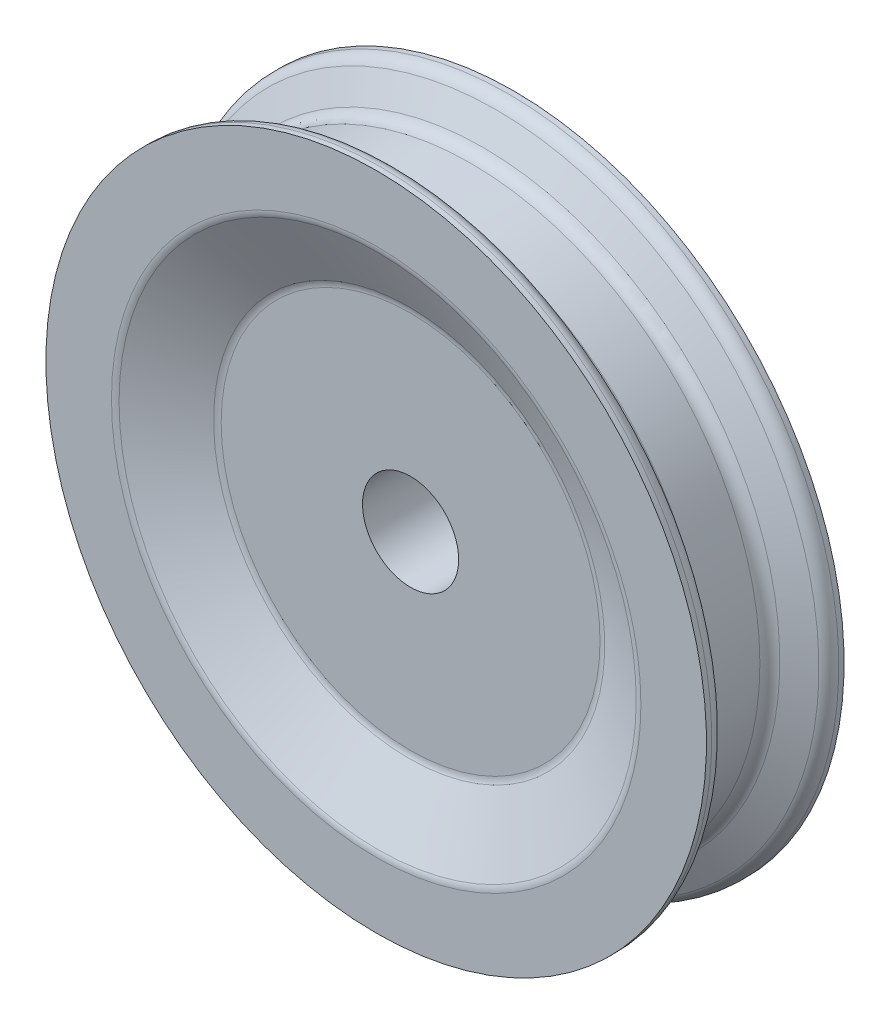
SolidWorks part; units mm, degrees
ref_plane "Front Plane" through (0, 0, 0) normal (0, 0, 1) x (1, 0, 0)
ref_plane "Top Plane" through (0, 0, 0) normal (0, 1, 0) x (1, 0, 0)
ref_plane "Right Plane" through (0, 0, 0) normal (1, 0, 0) x (0, 0, -1)
sketch "Sketch1" plane through (0, 0, 0) normal (1, 0, 0) x (0, 0, -1)
  line L0 (-25, 120) -> (-25, 95)
  line L1 (-12.5, 0) -> (12.5, 0)
  line L2 (25, 95) -> (25, 120)
  line L3 (-25, 120) -> (-20, 120)
  line L4 (-20, 120) -> (-12.5, 105)
  line L5 (-12.5, 105) -> (12.5, 105)
  line L6 (12.5, 105) -> (20, 120)
  line L7 (20, 120) -> (25, 120)
  line L8 (-25, 95) -> (-12.5, 70)
  line L9 (-12.5, 70) -> (-12.5, 0)
  line L10 (25, 95) -> (12.5, 70)
  line L11 (12.5, 70) -> (12.5, 0)
  point P2 (0, 0)
  point P6 (0, 105)
  dimension "D1" = 120
  dimension "D2" = 50
  dimension "D3" = 15
  dimension "D4" = 5
  dimension "D5" = 25
  dimension "D6" = 10
  dimension "D7" = 25
  dimension "D8" = 25
revolve "Main wheel extrude" add sketch "Sketch1" angle 360 about L1
fillet "Fillets" radius 5 8 edges at (0, -95, 25) (0, -70, 12.5) (0, -95, -25) (0, -70, -12.5) (0, -105, 12.5) (0, -105, -12.5) (0, -120, 20) (0, -120, -20)
sketch "Sketch3" plane through (0, 0, -12.5) normal (0, 0, -1) x (-1, 0, 0)
  circle A1 centre (0, 0) radius 17.4625
  dimension "D1" = 34.925
extrude "Shaft cut" cut sketch "Sketch3" against normal through all both and the other way through all
